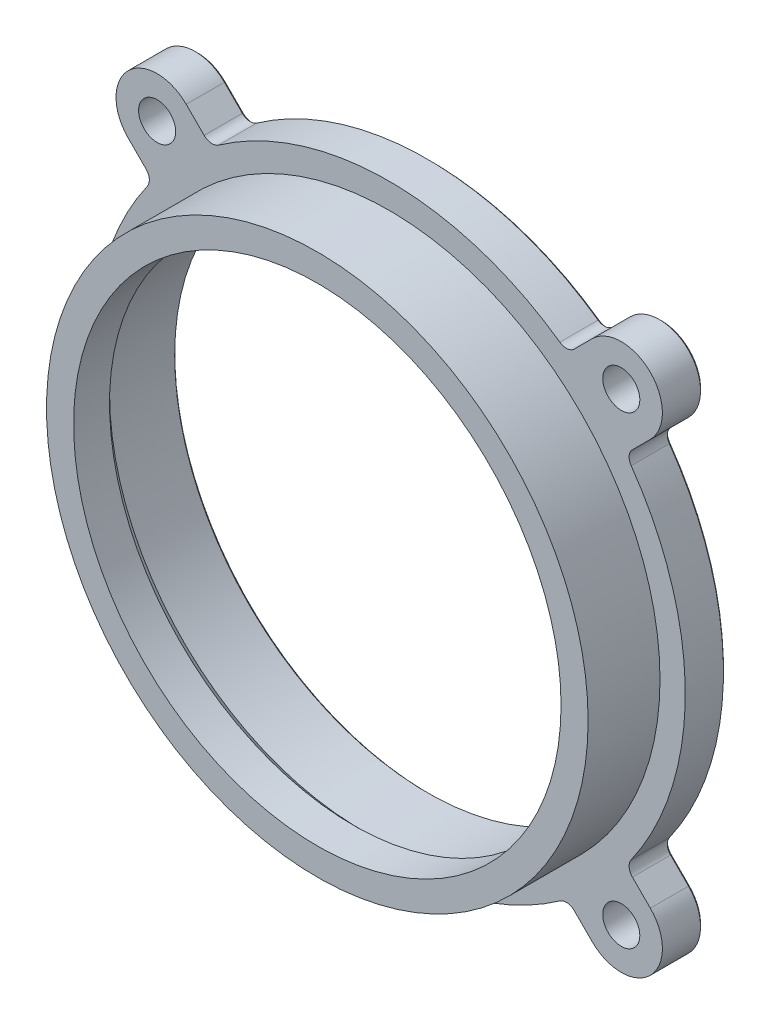
SolidWorks part; units mm, degrees
ref_plane "Front Plane" through (0, 0, 0) normal (0, 0, 1) x (1, 0, 0)
ref_plane "Top Plane" through (0, 0, 0) normal (0, 1, 0) x (1, 0, 0)
ref_plane "Right Plane" through (0, 0, 0) normal (1, 0, 0) x (0, 0, -1)
sketch "Sketch1" plane through (0, 0, 0) normal (0, 0, 1) x (1, 0, 0)
  line L49 (23.2497, 18.0736) -> (21.6518, 16.4758)
  line L50 (-23.2497, -18.0736) -> (-21.6518, -16.4758)
  line L51 (23.2497, -18.0736) -> (21.6518, -16.4758)
  line L52 (18.0736, -23.2497) -> (16.4758, -21.6518)
  line L57 (16.4758, 21.6518) -> (18.0736, 23.2497)
  line L62 (-16.4758, -21.6518) -> (-18.0736, -23.2497)
  line L63 (-21.6518, 16.4758) -> (-23.2497, 18.0736)
  line L64 (-16.4758, 21.6518) -> (-18.0736, 23.2497)
  arc A45 (-23.2497, -18.0736) -> (-18.0736, -23.2497) centre (-20.6617, -20.6617) ccw
  arc A46 (18.0736, -23.2497) -> (23.2497, -18.0736) centre (20.6617, -20.6617) ccw
  circle A47 centre (-20.6617, -20.6617) radius 1.65
  circle A48 centre (20.6617, -20.6617) radius 1.65
  circle A65 centre (0, 0) radius 21.6
  arc A71 (15.1923, 21.5417) -> (-15.1923, 21.5417) centre (0, 0) ccw
  arc A73 (21.5417, -15.1923) -> (21.5417, 15.1923) centre (0, 0) ccw
  circle A80 centre (20.6617, 20.6617) radius 1.65
  circle A81 centre (-20.6617, 20.6617) radius 1.65
  arc A82 (18.0736, 23.2497) -> (23.2497, 18.0736) centre (20.6617, 20.6617) cw
  arc A83 (-23.2497, 18.0736) -> (-18.0736, 23.2497) centre (-20.6617, 20.6617) cw
  arc A85 (-21.5417, 15.1923) -> (-21.5417, -15.1923) centre (0, 0) ccw
  arc A86 (-15.1923, -21.5417) -> (15.1923, -21.5417) centre (0, 0) ccw
  arc A87 (-15.1923, -21.5417) -> (-16.4758, -21.6518) centre (-15.7686, -22.3589) ccw
  arc A88 (-21.5417, -15.1923) -> (-21.6518, -16.4758) centre (-22.3589, -15.7686) cw
  arc A89 (-21.5417, 15.1923) -> (-21.6518, 16.4758) centre (-22.3589, 15.7686) ccw
  arc A90 (-15.1923, 21.5417) -> (-16.4758, 21.6518) centre (-15.7686, 22.3589) cw
  arc A91 (15.1923, -21.5417) -> (16.4758, -21.6518) centre (15.7686, -22.3589) cw
  arc A92 (21.5417, -15.1923) -> (21.6518, -16.4758) centre (22.3589, -15.7686) ccw
  arc A93 (15.1923, 21.5417) -> (16.4758, 21.6518) centre (15.7686, 22.3589) ccw
  arc A94 (21.6518, 16.4758) -> (21.5417, 15.1923) centre (22.3589, 15.7686) ccw
extrude "Boss-Extrude1" add sketch "Sketch1" along normal blind 3.6
sketch "Sketch4" plane through (0, 0, 3.6) normal (0, 0, 1) x (1, 0, 0)
  circle A7 centre (0, 0) radius 21.7
  circle A8 centre (0, 0) radius 24.11
extrude "Boss-Extrude2" add sketch "Sketch4" along normal offset from surface (6.4 mm away) 10 up to face at (0, 0, 0)
sketch "Sketch7" plane through (0, 0, 0) normal (0, 1, 0) x (1, 0, 0)
  line L4 (0, -10) -> (0, 0)
  line L6 (21.7, -10) -> (0, -10)
  line L7 (0, 0) -> (22.5, 0)
  line L9 (22.5, 0) -> (22.5, -6)
  line L10 (22.5, -6) -> (21.7, -6.8)
  line L11 (21.7, -6.8) -> (21.7, -10)
revolve "Cut-Revolve1" cut sketch "Sketch7" angle 360 about L4
chamfer "Chamfer1" distance 0.2 angle 45 29 edges at (-26.36, 0, 0) (-21.3625, -15.8541, 0) (-21.3625, 15.8541, 0) (-22.4507, -17.2747, 0) (-22.4507, 17.2747, 0) (-23.2497, -23.2497, 0) (-23.2497, 23.2497, 0) (-17.2747, -22.4507, 0) (-17.2747, 22.4507, 0) (-15.8541, -21.3625, 0) (-15.8541, 21.3625, 0) (0, -26.36, 0) (0, 26.36, 0) (15.8541, -21.3625, 0) (15.8541, 21.3625, 0) (17.2747, -22.4507, 0) (17.2747, 22.4507, 0) (23.2497, -23.2497, 0) (23.2497, 23.2497, 0) (22.4507, -17.2747, 0) (22.4507, 17.2747, 0) (21.3625, -15.8541, 0) (21.3625, 15.8541, 0) (26.36, 0, 0) (22.5, 0, 0) (-22.3117, 20.6617, 0) (-19.0117, -20.6617, 0) (22.3117, -20.6617, 0) (19.0117, 20.6617, 0)
